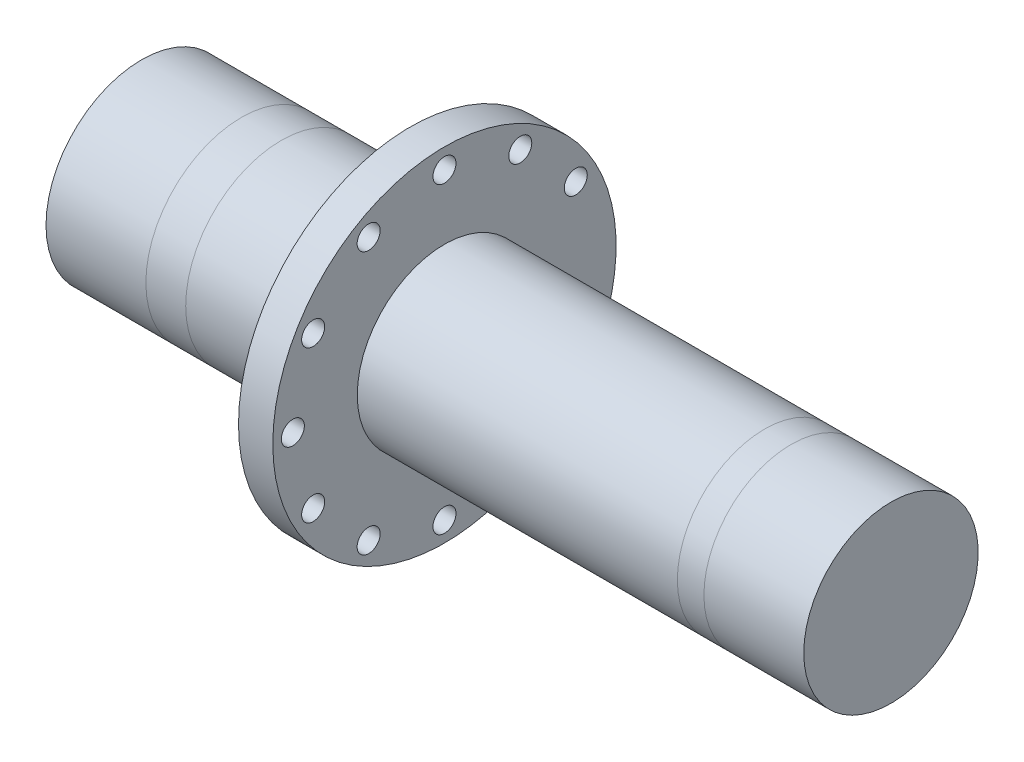
SolidWorks part; units mm, degrees
material "4140 Steel"
ref_plane "Front Plane" through (0, 0, 0) normal (0, 0, 1) x (1, 0, 0)
ref_plane "Top Plane" through (0, 0, 0) normal (0, 1, 0) x (1, 0, 0)
ref_plane "Right Plane" through (0, 0, 0) normal (1, 0, 0) x (0, 0, -1)
sketch "Sketch1" plane through (0, 0, 0) normal (0, 1, 0) x (1, 0, 0)
  line L0 (0, 0) -> (215, 0) construction
  line L1 (0, 0) -> (215, 0)
  line L2 (0, 0) -> (0, 27.432)
  line L3 (0, 27.432) -> (77.05, 27.432)
  line L4 (215, 0) -> (215, 25.019)
  line L5 (76.962, 0) -> (148.082, 0)
  line L6 (77.05, 27.432) -> (77.05, 49.25)
  line L7 (77.05, 49.25) -> (86.8925, 49.25)
  line L9 (148.198, 25.019) -> (215, 25.019)
  line L10 (86.8925, 49.25) -> (86.8925, 25.019)
  line L11 (86.8925, 25.019) -> (148.198, 25.019)
  dimension "D1" = 27.432
  dimension "D2" = 215
  dimension "D3" = 9.8425
  dimension "D4" = 77.05
  dimension "D5" = 25.019
  dimension "D6" = 49.25
revolve "Revolve1" add sketch "Sketch1" angle 360 about L1
sketch "Sketch2" plane through (77.05, 0, 0) normal (-1, 0, 0) x (0, 0, 1)
  line L0 (0, 0) -> (0, 43.5) construction
  circle A15 centre (0, 0) radius 43.5 construction
  circle A16 centre (0, 43.5) radius 3.2639
  circle A17 centre (21.75, 37.6721) radius 3.2639
  circle A18 centre (37.6721, 21.75) radius 3.2639
  circle A19 centre (43.5, 0) radius 3.2639
  circle A20 centre (37.6721, -21.75) radius 3.2639
  circle A21 centre (21.75, -37.6721) radius 3.2639
  circle A22 centre (0, -43.5) radius 3.2639
  circle A23 centre (-21.75, -37.6721) radius 3.2639
  circle A24 centre (-37.6721, -21.75) radius 3.2639
  circle A25 centre (-43.5, 0) radius 3.2639
  circle A26 centre (-37.6721, 21.75) radius 3.2639
  circle A27 centre (-21.75, 37.6721) radius 3.2639
  point P30 (0, 0)
  dimension "D2" = 6.5278
  dimension "D1" = 87
sketch "Sketch3" plane through (0, 0, 0) normal (-1, 0, 0) x (0, 0, 1)
  circle A0 centre (0, 0) radius 19.939
  dimension "D1" = 39.878
ref_plane "Plane1" through (28.65, 0, 0) normal (-1, 0, 0) x (0, 0, 1)
ref_plane "Plane2" through (40.08, 0, 0) normal (-1, 0, 0) x (0, 0, 1)
split line "Split Line1"
ref_plane "Plane3" through (186.35, 0, 0) normal (1, 0, 0) x (0, 0, -1)
ref_plane "Plane4" through (178.73, 0, 0) normal (1, 0, 0) x (0, 0, -1)
split line "Split Line2"
hole_wizard "M6 Clearance Hole1" positions "Sketch6" profile "Sketch7" hole size "M6" standard "ANSI Metric" end condition through all
sketch "Sketch6" plane through (77.05, -25.4169, -173.8609) normal (-1, 0, 0) x (0, 0.3427, 0.9395)
  point P0 (129.2008, -43.2203)
  point P1 (138.7033, -63.6343)
  point P2 (157.1396, -76.562)
  point P3 (179.5699, -78.5396)
  point P4 (199.9838, -69.0371)
  point P5 (212.9116, -50.6007)
  point P6 (214.8892, -28.1704)
  point P7 (205.3866, -7.7565)
  point P8 (186.9503, 5.1713)
  point P9 (164.52, 7.1488)
  point P10 (144.1061, -2.3537)
sketch "Sketch7" plane through (77.05, -21.75, -37.6721) normal (0, 1, 0) x (0, 0, 1)
  line L0 (0, 0) -> (0, 137.95)
  line L1 (0, 137.95) -> (3.3, 137.95)
  line L2 (3.3, 137.95) -> (3.3, 0)
  line L3 (3.3, 0) -> (0, 0)
  line L4 (0, -6.35) -> (0, 107.95) construction
  dimension "Thru Hole Dia." = 6.6
  dimension "Thru Hole Depth" = 137.95
